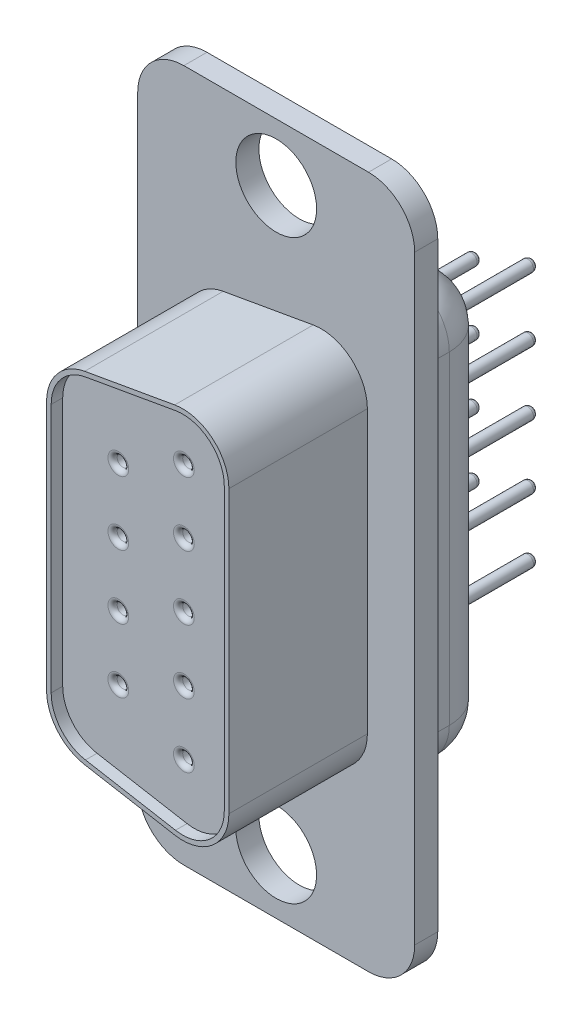
SolidWorks part; units mm, degrees
ref_plane "Спереди" through (0, 0, 0) normal (0, 0, 1) x (1, 0, 0)
ref_plane "Сверху" through (0, 0, 0) normal (0, 1, 0) x (1, 0, 0)
ref_plane "Справа" through (0, 0, 0) normal (1, 0, 0) x (0, 0, -1)
sketch "Эскиз1" plane through (0, 0, 0) normal (0, 0, 1) x (1, 0, 0)
  line L1 (0, 0) -> (12, 0)
  line L2 (0, 0) -> (0, 30)
  line L3 (0, 30) -> (12, 30)
  line L4 (12, 0) -> (12, 30)
  dimension "D1" = 30
  dimension "D2" = 12
extrude "Основание-Вытянуть" add sketch "Эскиз1" along normal blind 1
sketch "Эскиз2" plane through (0, 0, 1) normal (0, 0, 1) x (1, 0, 0)
  line L0 (6, 32.3343) -> (6, -1.805) construction
  line L1 (0, 30) -> (0, 0) construction
  line L2 (12, 0) -> (12, 30) construction
  line L3 (-3.7919, 15) -> (15.0641, 15) construction
  line L4 (12, 30) -> (0, 30) construction
  line L5 (0, 0) -> (12, 0) construction
  circle A0 centre (6, 27.5) radius 1.75
  circle A1 centre (6, 2.5) radius 1.75
  dimension "D1" = 3.5
  dimension "D2" = 25
extrude "Вырез-Вытянуть1" cut sketch "Эскиз2" against normal through all
sketch "Эскиз3" plane through (0, 0, 1) normal (0, 0, 1) x (1, 0, 0)
  line L0 (6, 31.856) -> (6, -1.0268) construction
  line L3 (-4.7857, 15) -> (16.0551, 15) construction
  line L6 (2.05, 9.5877) -> (2.05, 20.4123)
  line L7 (3.7027, 22.3819) -> (7.6027, 23.0696)
  line L8 (3.7027, 7.6181) -> (7.6027, 6.9304)
  line L9 (9.95, 21.1) -> (9.95, 8.9)
  line L10 (7.95, 23.1) -> (16.0551, 23.1) construction
  line L11 (7.95, 6.9) -> (18.5784, 6.9) construction
  line L12 (0, 30) -> (0, 0) construction
  line L13 (12, 0) -> (12, 30) construction
  line L14 (0, 0) -> (12, 0) construction
  line L15 (12, 30) -> (0, 30) construction
  arc A0 (9.95, 21.1) -> (7.6027, 23.0696) centre (7.95, 21.1) ccw
  arc A1 (7.6027, 6.9304) -> (9.95, 8.9) centre (7.95, 8.9) ccw
  arc A2 (3.7027, 7.6181) -> (2.05, 9.5877) centre (4.05, 9.5877) cw
  arc A3 (2.05, 20.4123) -> (3.7027, 22.3819) centre (4.05, 20.4123) cw
  point P7 (2.05, 15)
  point P10 (9.95, 15)
  dimension "D2" = 2
  dimension "D1" = 7.9
  dimension "D3" = 16.2
  dimension "D4" = 80
extrude "Бобышка-Вытянуть1" add sketch "Эскиз3" along normal blind 6
sketch "Эскиз4" plane through (0, 0, 0) normal (0, 0, -1) x (-1, 0, 0)
  line L0 (-8.0661, 23.9591) -> (-3.0661, 22.848)
  line L1 (-17.3136, 15) -> (4.5858, 15) construction
  line L2 (-12, 30) -> (0, 30) construction
  line L3 (0, 0) -> (-12, 0) construction
  line L4 (-8.0661, 6.0409) -> (-3.0661, 7.152)
  line L5 (-1.5, 20.8957) -> (-1.5, 9.1043)
  line L6 (-10.5, 22.0068) -> (-10.5, 7.9932)
  line L8 (-12, 0) -> (-12, 30) construction
  arc A1 (-8.0661, 23.9591) -> (-10.5, 22.0068) centre (-8.5, 22.0068) ccw
  arc A2 (-1.5, 20.8957) -> (-3.0661, 22.848) centre (-3.5, 20.8957) ccw
  arc A3 (-3.0661, 7.152) -> (-1.5, 9.1043) centre (-3.5, 9.1043) ccw
  arc A4 (-10.5, 7.9932) -> (-8.0661, 6.0409) centre (-8.5, 7.9932) ccw
  point P13 (-1.5, 15)
  point P14 (-10.5, 15)
  point P18 (-10.5, 24.5)
  point P21 (-1.5, 22.5)
  point P24 (-1.5, 7.5)
  point P27 (-10.5, 5.5)
  dimension "D5" = 2
  dimension "D1" = 15
  dimension "D2" = 1.5
  dimension "D3" = 9
  dimension "D4" = 19
extrude "Бобышка-Вытянуть2" add sketch "Эскиз4" along normal blind 4
sketch "Эскиз5" plane through (0, 0, -4) normal (0, 0, -1) x (-1, 0, 0)
  line L0 (-12, 0) -> (-12, 30) construction
  line L2 (-12, 30) -> (0, 30) construction
  circle A0 centre (-7.5, 15) radius 0.25
  dimension "D1" = 0.5
  dimension "D2" = 4.5
  dimension "D3" = 15
extrude "Бобышка-Вытянуть3" add sketch "Эскиз5" along normal blind 4.6
sketch "Эскиз6" plane through (0, 0, -4) normal (0, 0, -1) x (-1, 0, 0)
  circle A0 centre (-4.66, 16.385) radius 0.25
  circle A1 centre (-7.5, 15) radius 0.25 construction
  circle A2 centre (-7.5, 15) radius 0.25 construction
  dimension "D1" = 0.5
  dimension "D3" = 1.385
  dimension "D2" = 2.84
extrude "Бобышка-Вытянуть4" add sketch "Эскиз6" along normal blind 5
sketch "Эскиз8" plane through (0, 0, 7) normal (0, 0, 1) x (1, 0, 0)
  line L0 (12, 30) -> (0, 30) construction
  line L1 (12, 0) -> (12, 30) construction
  circle A0 centre (7.5, 15) radius 0.25
  dimension "D1" = 0.5
  dimension "D2" = 15
  dimension "D3" = 4.5
sketch "Эскиз9" plane through (0, 0, 7) normal (0, 0, 1) x (1, 0, 0)
  circle A0 centre (4.66, 16.385) radius 0.25
  dimension "D1" = 0.5
extrude "Вырез-Вытянуть4" cut sketch "Эскиз8" against normal blind 5
extrude "Вырез-Вытянуть5" cut sketch "Эскиз9" against normal blind 5
pattern_linear "Линейный массив3" count 3 spacing 2.77 along (0, 1, 0) count 3 spacing 2.77 along (0, -1, 0) of "Бобышка-Вытянуть3"
pattern_linear "Линейный массив4" count 3 spacing 2.77 along (0, -1, 0) count 2 spacing 2.77 along (0, 1, 0) of "Бобышка-Вытянуть4"
pattern_linear "Линейный массив5" count 3 spacing 2.77 along (0, -1, 0) count 3 spacing 2.77 along (0, 1, 0) of "Вырез-Вытянуть4"
pattern_linear "Линейный массив6" count 3 spacing 2.77 along (0, -1, 0) count 2 spacing 2.77 along (0, 1, 0) of "Вырез-Вытянуть5"
sketch "Эскиз14" plane through (0, 0, 7) normal (0, 0, 1) x (1, 0, 0)
  line L8 (7.6374, 22.8727) -> (3.7374, 22.185)
  line L9 (2.25, 20.4123) -> (2.25, 9.5877)
  line L10 (3.7374, 7.815) -> (7.6374, 7.1273)
  line L11 (9.75, 8.9) -> (9.75, 21.1)
  line L12 (7.6374, 22.8727) -> (3.7374, 22.185)
  line L13 (2.25, 20.4123) -> (2.25, 9.5877)
  line L14 (3.7374, 7.815) -> (7.6374, 7.1273)
  line L15 (9.75, 8.9) -> (9.75, 21.1)
  arc A9 (9.75, 21.1) -> (7.6374, 22.8727) centre (7.95, 21.1) ccw
  arc A10 (3.7374, 22.185) -> (2.25, 20.4123) centre (4.05, 20.4123) ccw
  arc A11 (2.25, 9.5877) -> (3.7374, 7.815) centre (4.05, 9.5877) ccw
  arc A12 (7.6374, 7.1273) -> (9.75, 8.9) centre (7.95, 8.9) ccw
  arc A13 (9.75, 21.1) -> (7.6374, 22.8727) centre (7.95, 21.1) ccw
  arc A14 (3.7374, 22.185) -> (2.25, 20.4123) centre (4.05, 20.4123) ccw
  arc A15 (2.25, 9.5877) -> (3.7374, 7.815) centre (4.05, 9.5877) ccw
  arc A16 (7.6374, 7.1273) -> (9.75, 8.9) centre (7.95, 8.9) ccw
  dimension "D1" = 0.2
extrude "Вырез-Вытянуть6" cut sketch "Эскиз14" against normal blind 0.5
fillet "Скругление1" radius 2 4 edges at (0, 0, 0.5) (0, 30, 0.5) (12, 30, 0.5) (12, 0, 0.5)
fillet "Скругление2" radius 2 8 edges at (9.7515, 6.4331, -4) (10.5, 15, -4) (9.7515, 23.5669, -4) (5.5661, 23.4036, -4) (1.9399, 22.1471, -4) (1.5, 15, -4) (1.9399, 7.8529, -4) (5.5661, 6.5964, -4)
fillet "Скругление3" radius 0.2 9 edges at (4.91, 19.155, 6.5) (4.91, 16.385, 6.5) (4.91, 13.615, 6.5) (4.91, 10.845, 6.5) (7.75, 9.46, 6.5) (7.75, 12.23, 6.5) (7.75, 15, 6.5) (7.75, 17.77, 6.5) (7.75, 20.54, 6.5)
fillet "Скругление4" radius 0.2 9 edges at (4.41, 19.155, -9) (4.41, 16.385, -9) (4.41, 13.615, -9) (4.41, 10.845, -9) (7.25, 9.46, -8.6) (7.25, 12.23, -8.6) (7.25, 15, -8.6) (7.25, 17.77, -8.6) (7.25, 20.54, -8.6)
sketch "Эскиз17" plane through (0, 0, 0) normal (0, -1, 0) x (1, 0, 0)
  line L1 (10, 1) -> (1.9926, 1)
  line L2 (10, 1) -> (10, 1.5)
  line L3 (10, 1.5) -> (1.9926, 1.5)
  line L4 (1.9926, 1) -> (1.9926, 1.5)
  dimension "D1" = 0.5
sketch "Эскиз18" plane through (0, 30, 0) normal (0, 1, 0) x (1, 0, 0)
  line L1 (10, -1) -> (2, -1)
  line L2 (10, -1) -> (10, -1.5)
  line L3 (10, -1.5) -> (2, -1.5)
  line L4 (2, -1) -> (2, -1.5)
  dimension "D1" = 0.5
